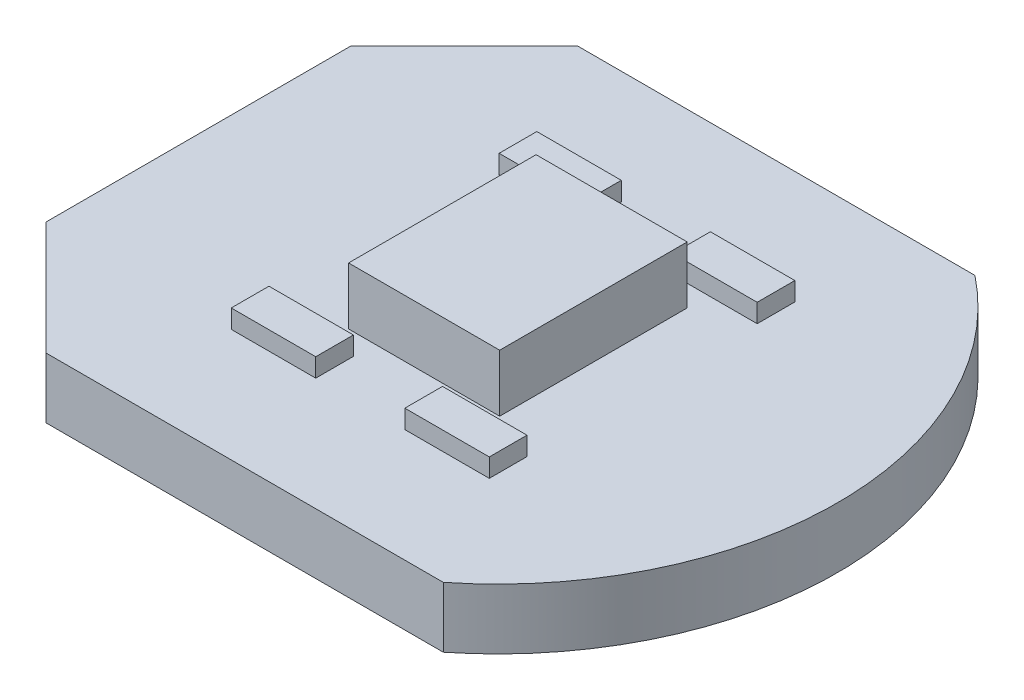
SolidWorks part; units mm, degrees
ref_plane "Front" through (0, 0, 0) normal (0, 0, 1) x (1, 0, 0)
ref_plane "Top" through (0, 0, 0) normal (0, 1, 0) x (1, 0, 0)
ref_plane "Right" through (0, 0, 0) normal (1, 0, 0) x (0, 0, -1)
sketch "Sketch1" plane through (0, 0, 0) normal (0, 1, 0) x (1, 0, 0)
  line L0 (-8.605, 4.105) -> (-8.605, -4.105)
  line L1 (-8.605, -7.16) -> (8.605, -7.16) construction
  line L2 (-8.605, -7.16) -> (-8.605, 7.16) construction
  line L3 (-8.605, 7.16) -> (8.605, 7.16) construction
  line L4 (8.605, -7.16) -> (8.605, 7.16) construction
  line L5 (-8.605, -7.16) -> (8.605, 7.16) construction
  line L6 (-8.605, 7.16) -> (8.605, -7.16) construction
  line L7 (-8.605, -4.105) -> (-5.55, -7.16)
  line L8 (-5.55, -7.16) -> (5.15, -7.16)
  line L9 (-8.605, 4.105) -> (-5.55, 7.16)
  line L10 (-5.55, 7.16) -> (5.15, 7.16)
  arc A0 (5.15, 7.16) -> (5.15, -7.16) centre (-0.5415, 0) cw
  point P0 (0, 0)
  dimension "D5" = 10.7
  dimension "D1" = 14.32
  dimension "D2" = 17.21
  dimension "D3" = 45
  dimension "D4" = 8.21
extrude "Boss-Extrude1" add sketch "Sketch1" along normal blind 1.63
sketch "Sketch2" plane through (0, 1.63, 0) normal (0, 1, 0) x (1, 0, 0)
  line L1 (-2.035, -2.525) -> (2.035, -2.525)
  line L2 (-2.035, -2.525) -> (-2.035, 2.525)
  line L3 (-2.035, 2.525) -> (2.035, 2.525)
  line L4 (2.035, -2.525) -> (2.035, 2.525)
  line L5 (-2.035, -2.525) -> (2.035, 2.525) construction
  line L6 (-2.035, 2.525) -> (2.035, -2.525) construction
  point P0 (0, 0)
  point P5 (0, 0)
  point P7 (1.6607, 0)
  point P8 (0, 0)
  dimension "D1" = 5.05
  dimension "D2" = 4.07
extrude "Boss-Extrude2" add sketch "Sketch2" along normal blind 1.54
sketch "Sketch3" plane through (0, 1.63, 0) normal (0, 1, 0) x (1, 0, 0)
  line L0 (-8.605, 4.105) -> (-8.605, -4.105) construction
  line L1 (-3.605, -4.115) -> (3.345, -4.115) construction
  line L2 (-3.605, -4.115) -> (-3.605, 4.115) construction
  line L3 (-3.605, 4.115) -> (3.345, 4.115) construction
  line L4 (3.345, -4.115) -> (3.345, 4.115) construction
  line L5 (-3.605, -4.115) -> (3.345, 4.115) construction
  line L6 (-3.605, 4.115) -> (3.345, -4.115) construction
  line L7 (-3.605, 4.115) -> (-1.33, 4.115)
  line L8 (-3.605, 4.115) -> (-3.605, 3.1)
  line L9 (-3.605, 3.1) -> (-1.33, 3.1)
  line L10 (-1.33, 4.115) -> (-1.33, 3.1)
  line L11 (3.345, 4.115) -> (1.07, 4.115)
  line L12 (3.345, 4.115) -> (3.345, 3.1)
  line L13 (3.345, 3.1) -> (1.07, 3.1)
  line L14 (1.07, 4.115) -> (1.07, 3.1)
  line L15 (-3.605, -4.115) -> (-1.33, -4.115)
  line L16 (-3.605, -4.115) -> (-3.605, -3.1)
  line L17 (-3.605, -3.1) -> (-1.33, -3.1)
  line L18 (-1.33, -4.115) -> (-1.33, -3.1)
  line L19 (3.345, -4.115) -> (1.07, -4.115)
  line L20 (3.345, -4.115) -> (3.345, -3.1)
  line L21 (3.345, -3.1) -> (1.07, -3.1)
  line L22 (1.07, -4.115) -> (1.07, -3.1)
  point P0 (-0.13, 0)
  point P18 (-2.4301, 3.1)
  dimension "D1" = 6.95
  dimension "D2" = 8.23
  dimension "D3" = 6.2
  dimension "D4" = 2.4
  dimension "D5" = 5
extrude "Boss-Extrude3" add sketch "Sketch3" along normal blind 0.5
